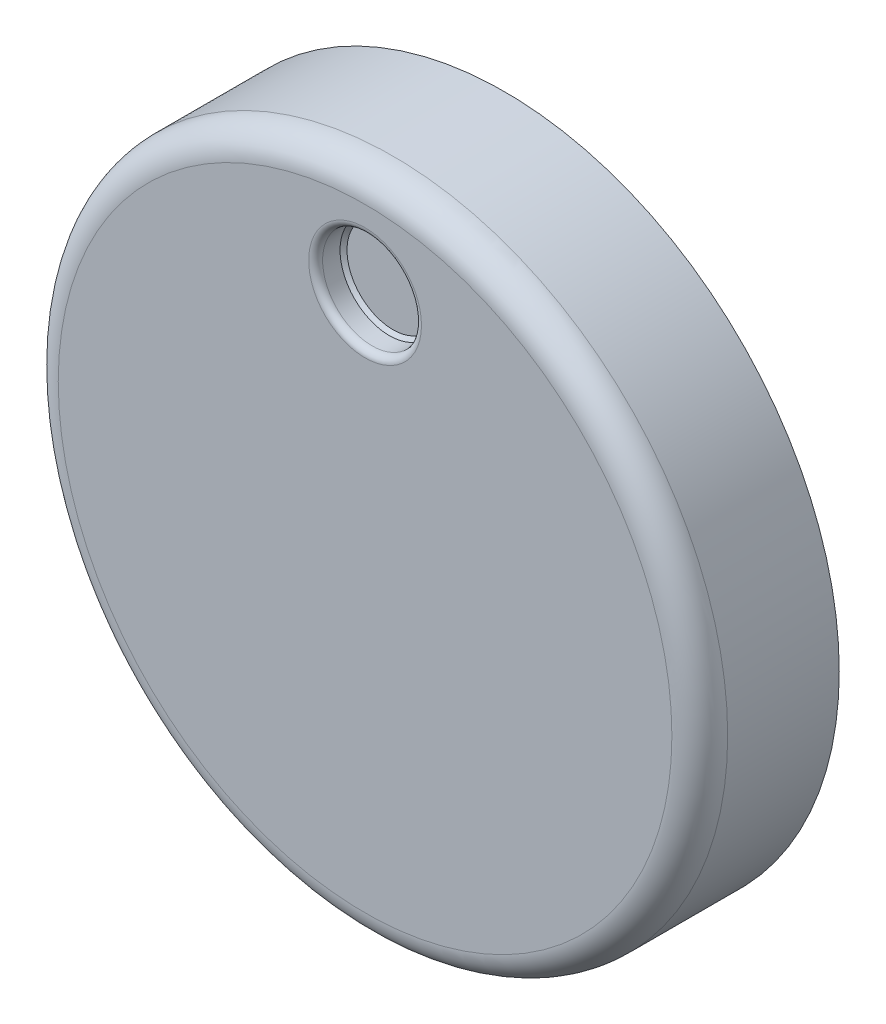
SolidWorks part; units mm, degrees
material "moto_white"
ref_plane "Front Plane" through (0, 0, 0) normal (0, 0, 1) x (1, 0, 0)
ref_plane "Top Plane" through (0, 0, 0) normal (0, 1, 0) x (1, 0, 0)
ref_plane "Right Plane" through (0, 0, 0) normal (1, 0, 0) x (0, 0, -1)
sketch "Sketch1" plane through (0, 0, 0) normal (0, 0, 1) x (1, 0, 0)
  circle A0 centre (0, 0) radius 48
  dimension "D1" = 96
extrude "Boss-Extrude1" add sketch "Sketch1" against normal blind 20
fillet "Fillet1" radius 4 1 edges at (48, 0, 0)
sketch "Sketch2" plane through (0, 0, 0) normal (0, 0, 1) x (1, 0, 0)
  circle A0 centre (0, 33.0157) radius 7.089
extrude "Cut-Extrude1" cut sketch "Sketch2" against normal blind 4 contours A0
fillet "Fillet3" radius 1 1 edges at (7.089, 33.0157, 0)
chamfer "Chamfer1" distance 0.5 angle 45 1 edges at (7.089, 33.0157, -4)
